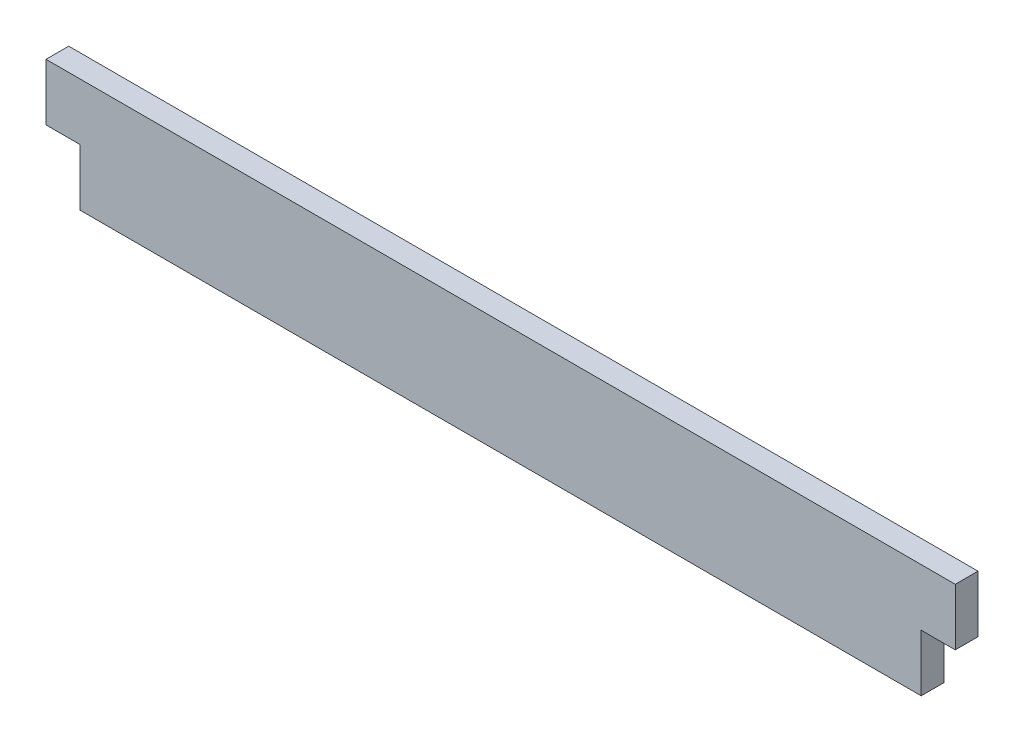
SolidWorks part; units mm, degrees
ref_plane "Front Plane" through (0, 0, 0) normal (0, 0, 1) x (1, 0, 0)
ref_plane "Top Plane" through (0, 0, 0) normal (0, 1, 0) x (1, 0, 0)
ref_plane "Right Plane" through (0, 0, 0) normal (1, 0, 0) x (0, 0, -1)
sketch "Sketch1" plane through (0, 0, 0) normal (0, 0, 1) x (1, 0, 0)
  line L1 (40, -5) -> (-40, -5)
  line L2 (40, -5) -> (40, 5)
  line L3 (40, 5) -> (-40, 5)
  line L4 (-40, -5) -> (-40, 5)
  line L5 (40, -5) -> (-40, 5) construction
  line L6 (40, 5) -> (-40, -5) construction
  point P0 (0, 0)
  dimension "D1" = 10
  dimension "D2" = 80
extrude "Boss-Extrude2" add sketch "Sketch1" along normal blind 2
sketch "Sketch4" plane through (0, 0, 0) normal (0, 0, -1) x (-1, 0, 0)
  line L0 (40, 0) -> (37, 0)
  line L1 (40, 5) -> (40, -5) construction
  line L2 (37, 0) -> (37, -5)
  line L3 (40, -5) -> (-40, -5) construction
  line L4 (37, -5) -> (40, -5)
  line L5 (40, -5) -> (40, 0)
  line L6 (0, 0) -> (0, -5) construction
  line L7 (-40, -5) -> (-40, 0)
  line L8 (-37, -5) -> (-40, -5)
  line L9 (-37, 0) -> (-37, -5)
  line L10 (-40, 0) -> (-37, 0)
  dimension "D1" = 5
  dimension "D2" = 3
extrude "Cut-Extrude3" cut sketch "Sketch4" against normal through all
